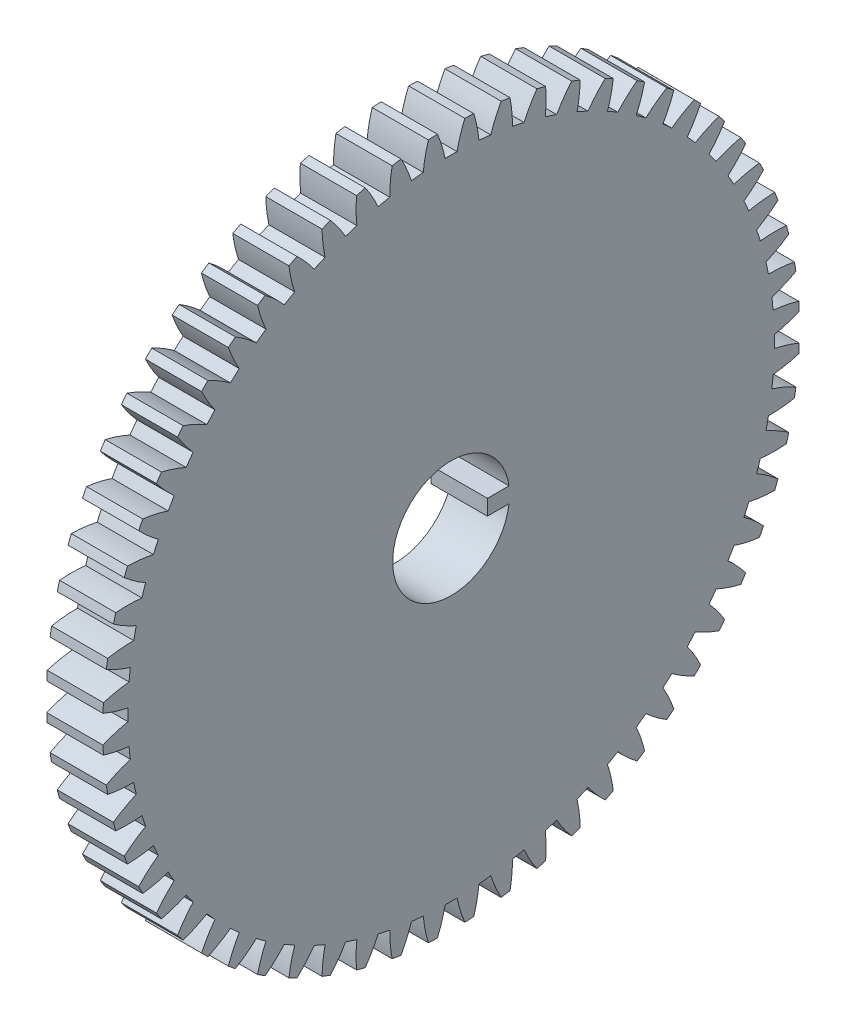
SolidWorks part; units mm, degrees
ref_plane "Plane1" through (0, 0, 0) normal (0, 0, 1) x (1, 0, 0)
ref_plane "Plane2" through (0, 0, 0) normal (0, 1, 0) x (1, 0, 0)
ref_plane "Plane3" through (0, 0, 0) normal (1, 0, 0) x (0, 0, -1)
sketch "HoldingSke" plane through (0, 0, 0) normal (0, 1, 0) x (1, 0, 0)
  line L0 (0, 0) -> (254, -439.9409)
  line L1 (-15, 0) -> (100, 0) construction
  line L2 (0, 0) -> (-2.1039, 2.3779)
  line L3 (0, 0) -> (-11.863, 4.5341)
  line L4 (0, 0) -> (4.318, 7.479)
  line L5 (0, 0) -> (-47.5972, -17.7524)
  line L6 (0, 0) -> (-5.2639, -3.5516)
  line L7 (-2.1039, 2.3779) -> (8.8308, 51.9871)
  line L8 (-76.2, 54.61) -> (-65.4837, 54.61)
  line L9 (-67.7845, 28.3722) -> (-49.3413, 33.142)
  line L10 (-76.2, 71.12) -> (104.1128, 71.12)
  line L11 (0, 0) -> (-6.35, 0)
  line L12 (-76.2, 101.6) -> (-76.1492, 101.6)
  line L13 (24.9733, 27.94) -> (52.9518, 28.4284)
  line L14 (24.9733, 27.94) -> (25.0241, 27.9398)
  line L15 (24.9733, 27.94) -> (100.4021, 29.52)
  circle A0 centre (0, 0) radius 4.7625
  circle A1 centre (0, 0) radius 36.5252
  circle A2 centre (0, 0) radius 38.1
  circle A3 centre (0, 0) radius 4.7625
  dimension "MHD" = 73.0504
  dimension "Hub_dia" = 76.2
  dimension "Bore" = 9.525
  dimension "MBD" = 9.525
  dimension "Num_teeth" = 60
  dimension "Pitch" = 508
  dimension "Overall_len" = 50.8
  dimension "Show_teeth" = 60
  dimension "Thickness" = 6.35
  dimension "OAL" = 50.8001
  dimension "T_dim" = 10.7163
  dimension "Ap" = 14.5
  dimension "H" = 19.05
  dimension "Pitch_radius" = 180.3128
  dimension "Width" = 6.35
  dimension "Backlash" = 0.0508
  dimension "Addendum_fac" = 1
  dimension "Dedendum_fac" = 1.2
  dimension "Clearance_fac" = 0.2
  dimension "Dedendum_add" = 0.0508
sketch "BasProSke" plane through (0, 0, 0) normal (0, 1, 0) x (1, 0, 0)
  line L0 (-10, 0) -> (60, 0) construction
  line L1 (0, 0) -> (0, 39.37)
  line L2 (0, 0) -> (6.35, 0)
  line L3 (6.35, 0) -> (6.35, 39.37)
  line L4 (6.35, 39.37) -> (0, 39.37)
  dimension "Thickness" = 6.35
  dimension "Diameter" = 78.74
revolve "Base-Revolve" add sketch "BasProSke" angle 360 about L0
sketch "TooCutSke" plane through (0, 0, 0) normal (1, 0, 0) x (0, 0, -1)
  line L1 (0, 0) -> (0, 107) construction
  line L2 (0, 0) -> (-1.0862, 38.0845) construction
  line L3 (0, 0) -> (-3.9869, 76.0739) construction
  line L4 (-1.0862, 38.0845) -> (-1.9934, 38.037) construction
  arc A0 (0.674, 36.519) -> (-0.674, 36.519) centre (0, 0) ccw
  arc A1 (1.5613, 39.3644) -> (-1.5613, 39.3644) centre (0, 0) ccw
  circle A2 centre (0, 0) radius 38.1 construction
  circle A3 centre (0, 0) radius 36.8864 construction
  arc A4 (-0.674, 36.519) -> (-1.5613, 39.3644) centre (-15.597, 33.4267) ccw
  arc A5 (1.5613, 39.3644) -> (0.674, 36.519) centre (15.597, 33.4267) ccw
  dimension "Root_dia" = 73.0504
  dimension "Overcut_dia" = 78.7908
  dimension "Pitch_dia" = 76.2
  dimension "Base_dia" = 73.7729
  dimension "Flank_rad" = 15.24
  dimension "Half_ang" = 3
  dimension "Half_CT" = 0.9084
extrude "ToothCut" cut sketch "TooCutSke" along normal through all
fillet "Breaks" [suppressed] radius 0.0254
fillet "RootFillets" [suppressed] radius 0.3048
pattern_circular "TeethCuts" count 60 every 6 about axis through (-10, 0, 0) along (1, 0, 0) of "ToothCut", "RootFillets", "Breaks"
sketch "HubNeaOneSke" plane through (0, 0, 0) normal (-1, 0, 0) x (0, 0, 1)
  circle A0 centre (0, 0) radius 36.5252
  dimension "Diameter" = 73.0504
extrude "HubNearOne" [suppressed] add sketch "HubNeaOneSke" along normal blind 44.4501
sketch "HubNeaBotSke" plane through (0, 0, 0) normal (-1, 0, 0) x (0, 0, 1)
  circle A0 centre (0, 0) radius 36.5252
  dimension "Diameter" = 73.0504
extrude "HubNearBoth" [suppressed] add sketch "HubNeaBotSke" along normal blind 22.225
ref_plane "FarPln" through (6.35, 0, 0) normal (1, 0, 0) x (0, 0, -1)
sketch "HubFarSke" plane through (6.35, 0, 0) normal (1, 0, 0) x (0, 0, -1)
  circle A0 centre (0, 0) radius 36.5252
  dimension "Diameter" = 73.0504
extrude "HubFar" [suppressed] add sketch "HubFarSke" along normal blind 22.225
sketch "BorSke" plane through (0, 0, 0) normal (1, 0, 0) x (0, 0, -1)
  circle A0 centre (0, 0) radius 6.604
  dimension "D1" = 13.208
extrude "Bore" cut sketch "BorSke" along normal mid plane 101.6001
sketch "KeySke" plane through (0, 0, 0) normal (1, 0, 0) x (0, 0, -1)
  line L0 (-1.1913, 0) -> (-1.1913, 5.9538)
  line L1 (-1.1913, 5.9538) -> (1.1913, 5.9538)
  line L2 (1.1913, 5.9538) -> (1.1913, 0)
  line L3 (0, 0) -> (0, 34) construction
  line L4 (-1.1913, 0) -> (1.1913, 0)
  dimension "Offset" = 5.9538
  dimension "Width" = 2.3825
extrude "Keyway" [suppressed] cut sketch "KeySke" along normal mid plane 101.6001
pattern_circular "Keyway2" [suppressed] count 2 every 90 about axis through (-10, 0, 0) along (1, 0, 0)
sketch "Sketch1" plane through (6.35, 0, 0) normal (1, 0, 0) x (0, 0, -1)
  line L0 (6.604, 0) -> (4.104, 0) construction
  line L1 (4.104, -0.875) -> (4.104, 0.875)
  line L2 (4.104, 0.875) -> (6.5458, 0.875)
  line L3 (4.104, -0.875) -> (6.5458, -0.875)
  circle A0 centre (0, 0) radius 6.604 construction
  circle A1 centre (0, 0) radius 6.604
  point P8 (4.104, 0)
  dimension "D1" = 2.5
  dimension "D2" = 1.75
extrude "Boss-Extrude1" add sketch "Sketch1" against normal blind 6.35 contours L0 A1 L2 L1 | A1 L0 L1 L3
equation "' \"Pitch@HoldingSke\" = 4"
equation "' \"Num_teeth@HoldingSke\" = 12"
equation "' \"Ap@HoldingSke\" =  20"
equation "' \"Ap@HoldingSke\" = 20"
equation "' \"Width@HoldingSke\" = 0.5"
equation "' \"Hub_dia@HoldingSke\"= 1"
equation "' \"Hub_dia@HoldingSke\" = 1"
equation "' \"Overall_len@HoldingSke\" = 1.0"
equation "' \"Bore@HoldingSke\" = 0.75"
equation "' \"T_dim@HoldingSke\" = 0.85"
equation "' \"Width@KeySke\" = 0.25"
equation "' \"Show_teeth@HoldingSke\" = 13"
equation "' \"Backlash@HoldingSke\" = 0.009"
equation "' \"Addendum_fac@HoldingSke\" = 1.0"
equation "' \"Dedendum_fac@HoldingSke\" = 1.25"
equation "' \"Dedendum_add@HoldingSke\" = 0.00005"
equation "' \"Clearance_fac@HoldingSke\" = 0.25"
equation "' \"Pitch@HoldingSke\" = 0.5"
equation "' \"Num_teeth@HoldingSke\" = 23"
equation "' \"Show_teeth@HoldingSke\" = 23"
equation "' \"Backlash@HoldingSke\" = 0.0375"
equation "\"Overcut_dia@TooCutSke\" = (\"Num_teeth@HoldingSke\" + 2 * \"Addendum_fac@HoldingSke\") / \"Pitch@HoldingSke\" + 0.002"
equation "\"Pitch_dia@TooCutSke\" = \"Num_teeth@HoldingSke\" / \"Pitch@HoldingSke\""
equation "\"Base_dia@TooCutSke\" = \"Num_teeth@HoldingSke\" / \"Pitch@HoldingSke\" * cos((\"Ap@HoldingSke\"  * 3.14159265 / 180))"
equation "\"Root_dia@TooCutSke\" = (\"Num_teeth@HoldingSke\" + 2) / \"Pitch@HoldingSke\" - 2 * (\"Addendum_fac@HoldingSke\" + \"Dedendum_fac@HoldingSke\") / \"Pitch@HoldingSke\" - \"Dedendum_add@HoldingSke\" * 2"
equation "\"Half_ang@TooCutSke\" = 180 / \"Num_teeth@HoldingSke\""
equation "\"Half_CT@TooCutSke\" = \"Num_teeth@HoldingSke\" / \"Pitch@HoldingSke\" * sin((3.14159265 / 2 / \"Num_teeth@HoldingSke\")) / 2 - 7 * \"Backlash@HoldingSke\" / 4"
equation "\"Flank_rad@TooCutSke\" = \"Num_teeth@HoldingSke\" / \"Pitch@HoldingSke\" / 5"
equation "\"Radius@RootFillets\" = \"Clearance_fac@HoldingSke\" / \"Pitch@HoldingSke\" + \"Dedendum_add@HoldingSke\""
equation "\"Break_rad@Breaks\" = 0.02 / \"Pitch@HoldingSke\""
equation "\"Thickness@HoldingSke\" = \"Width@HoldingSke\""
equation "\"OAL@HoldingSke\" = \"Thickness@HoldingSke\""
equation "\"MHD@HoldingSke\" = (\"Num_teeth@HoldingSke\" + 2) / \"Pitch@HoldingSke\" - 2 * (\"Addendum_fac@HoldingSke\" + \"Dedendum_fac@HoldingSke\")  / \"Pitch@HoldingSke\" - \"Dedendum_add@HoldingSke\" * 2"
equation "\"MBD@HoldingSke\" = (\"Num_teeth@HoldingSke\" + 2) / \"Pitch@HoldingSke\" - 2 * (\"Addendum_fac@HoldingSke\" + \"Dedendum_fac@HoldingSke\")  / \"Pitch@HoldingSke\" - \"Dedendum_add@HoldingSke\" * 2 - 0.002"
equation "\"MHD@HoldingSke\" = ((sgn( \"MHD@HoldingSke\" - \"Hub_dia@HoldingSke\" )-1)*( \"MHD@HoldingSke\" - \"Hub_dia@HoldingSke\" ))/-2+ \"Hub_dia@HoldingSke\""
equation "\"MBD@HoldingSke\" = ((sgn( \"MBD@HoldingSke\" - \"Bore@HoldingSke\" )-1)*( \"MBD@HoldingSke\" - \"Bore@HoldingSke\" ))/-2+ \"Bore@HoldingSke\""
equation "\"OAL@HoldingSke\" = ((sgn( \"OAL@HoldingSke\" - \"Overall_len@HoldingSke\" )+1)*( \"OAL@HoldingSke\" - \"Overall_len@HoldingSke\" ))/2 + \"Overall_len@HoldingSke\" + 0.000002"
equation "\"Num_teeth@TeethCuts\" = int( \"Show_teeth@HoldingSke\" ) + 1"
equation "\"Num_teeth@TeethCuts\" = ((sgn( \"Num_teeth@TeethCuts\" - \"Num_teeth@HoldingSke\" )-1)*( \"Num_teeth@TeethCuts\" - \"Num_teeth@HoldingSke\" ))/-2+ \"Num_teeth@HoldingSke\""
equation "\"Num_teeth@TeethCuts\" = ((sgn( \"Num_teeth@TeethCuts\" - 2.0)+1)*( \"Num_teeth@TeethCuts\" - 2.0))/2 +2.0"
equation "\"Angle@TeethCuts\" = 360.0 / \"Num_teeth@HoldingSke\""
equation "\"Diameter@BasProSke\" = (\"Num_teeth@HoldingSke\" + 2 * \"Addendum_fac@HoldingSke\") / \"Pitch@HoldingSke\""
equation "\"Thickness@BasProSke\"  = \"Thickness@HoldingSke\""
equation "' \"Fillet_rad@BasProSke\" =  \"Thickness@HoldingSke\" * 0.05"
equation "' \"Fillet_rad@BasProSke\" = \"Thickness@HoldingSke\" * 0.05"
equation "\"MHD@HoldingSke\" = ((sgn( \"MHD@HoldingSke\" - \"Root_dia@TooCutSke\" )-1)*( \"MHD@HoldingSke\" - \"Root_dia@TooCutSke\" ))/-2+ \"Root_dia@TooCutSke\""
equation "\"Diameter@HubNeaOneSke\" = \"MHD@HoldingSke\""
equation "\"Length@HubNearOne\" = \"OAL@HoldingSke\" - \"Thickness@BasProSke\""
equation "\"Diameter@HubNeaBotSke\" = \"MHD@HoldingSke\""
equation "\"Length@HubNearBoth\" = ( \"OAL@HoldingSke\" - \"Thickness@BasProSke\" ) / 2.0"
equation "\"Thickness@FarPln\" = \"Thickness@BasProSke\""
equation "\"Diameter@HubFarSke\" = \"MHD@HoldingSke\""
equation "\"Length@HubFar\" = ( \"OAL@HoldingSke\" - \"Thickness@BasProSke\" ) / 2.0"
equation "\"D1@Bore\" = \"OAL@HoldingSke\" * 2.0"
equation "\"D1@Keyway\" = \"OAL@HoldingSke\" * 2.0"
equation "\"Offset@KeySke\" = \"T_dim@HoldingSke\" - \"MBD@HoldingSke\" / 2.0"
